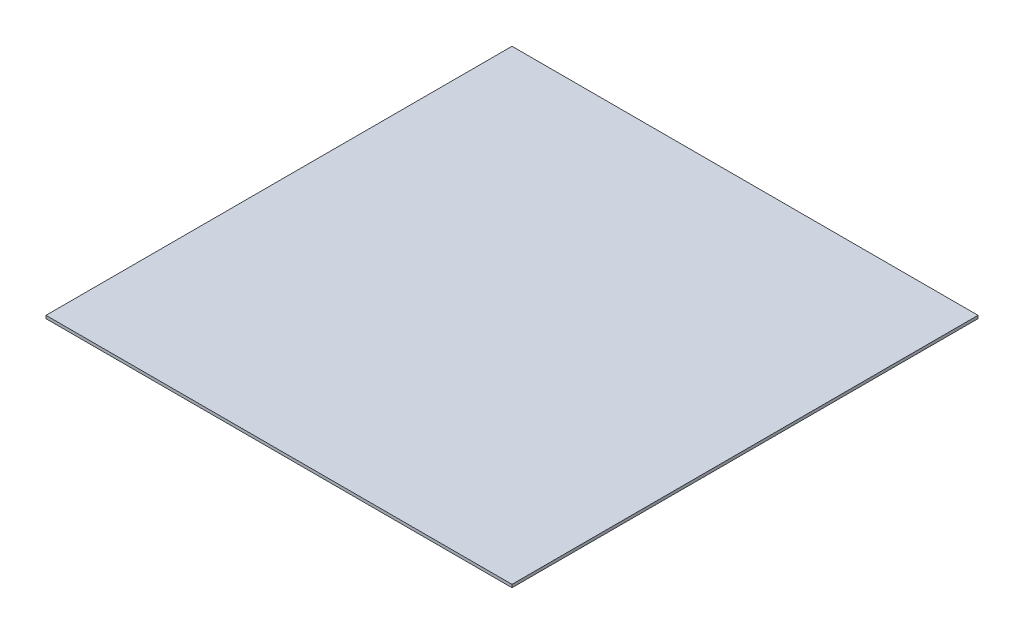
SolidWorks part; units mm, degrees
ref_plane "Front Plane" through (0, 0, 0) normal (0, 0, 1) x (1, 0, 0)
ref_plane "Top Plane" through (0, 0, 0) normal (0, 1, 0) x (1, 0, 0)
ref_plane "Right Plane" through (0, 0, 0) normal (1, 0, 0) x (0, 0, -1)
other "Configuration Table"
sketch "Sketch1" plane through (0, 0, 0) normal (0, 0, 1) x (1, 0, 0)
  line L1 (192, 506) -> (508, 506)
  line L2 (192, 506) -> (192, 508)
  line L3 (192, 508) -> (508, 508)
  line L4 (508, 506) -> (508, 508)
extrude "PACK_plunger_plakasi_316x316x2_1" add sketch "Sketch1" against normal blind 316 from offset 242 separate body
